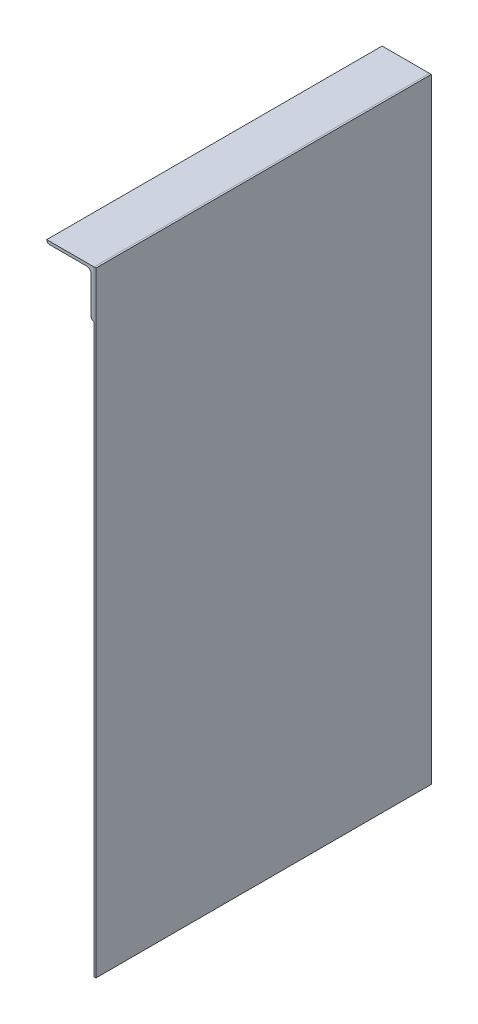
SolidWorks part; units mm, degrees
material "Fundición maleable"
ref_plane "Alzado" through (0, 0, 0) normal (0, 0, 1) x (1, 0, 0)
ref_plane "Planta" through (0, 0, 0) normal (0, 1, 0) x (1, 0, 0)
ref_plane "Vista lateral" through (0, 0, 0) normal (1, 0, 0) x (0, 0, -1)
sketch "Croquis1" plane through (0, 0, 0) normal (1, 0, 0) x (0, 0, -1)
  line L0 (0, 0) -> (-360, 0)
  line L1 (0, 0) -> (0, -660)
  dimension "D1" = 660
  dimension "D2" = 360
other "Hierro angular 2 X 2 X 0.125(1)"
ref_plane "Plano1" through (0, 0, 0) normal (0, 0, 1) x (-1, 0, 0)
sketch "Sketch1" plane through (0, 0, 0) normal (0, 0, 1) x (-1, 0, 0)
  line L0 (0, 0) -> (0, 50.8)
  line L1 (0, 50.8) -> (0.0051, 50.8)
  line L2 (3.175, 47.6301) -> (3.175, 7.9375)
  line L3 (7.9375, 3.175) -> (47.6301, 3.175)
  line L4 (50.8, 0.0051) -> (50.8, 0)
  line L5 (50.8, 0) -> (0, 0)
  arc A0 (50.8, 0.0051) -> (47.6301, 3.175) centre (47.6301, 0.0051) ccw
  arc A1 (0.0051, 50.8) -> (3.175, 47.6301) centre (0.0051, 47.6301) cw
  arc A2 (7.9375, 3.175) -> (3.175, 7.9375) centre (7.9375, 7.9375) cw
  point P10 (25.4, 0)
  point P14 (0, 25.4)
  point P15 (3.175, 25.4)
  point P16 (25.4, 3.175)
  point P17 (3.175, 50.8)
  point P18 (50.8, 3.175)
  point P19 (0, 0)
  dimension "D2" = 0.0051
  dimension "Radius_1" = 4.7625
  dimension "D1" = 3.175
  dimension "H_leg" = 50.8
sketch "Croquis2" plane through (0, 0, 0) normal (1, 0, 0) x (0, 0, -1)
  line L1 (0, 0) -> (-360, 0)
  line L2 (0, 0) -> (0, -660)
  line L3 (0, -660) -> (-360, -660)
  line L4 (-360, 0) -> (-360, -660)
extrude "Saliente-Extruir1" add sketch "Croquis2" along normal blind 2 separate body
